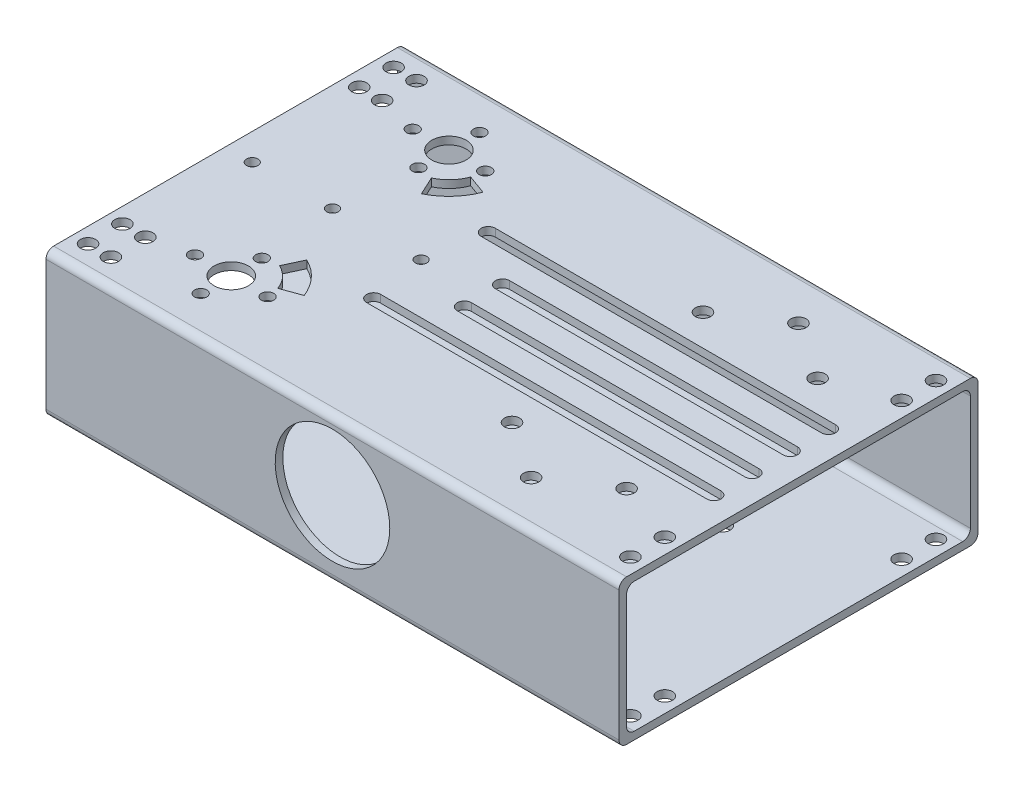
SolidWorks part; units mm, degrees
ref_plane "前视基准面" through (0, 0, 0) normal (0, 0, 1) x (1, 0, 0)
ref_plane "上视基准面" through (0, 0, 0) normal (0, 1, 0) x (1, 0, 0)
ref_plane "右视基准面" through (0, 0, 0) normal (1, 0, 0) x (0, 0, -1)
sketch "草图1" plane through (0, 0, 0) normal (0, 1, 0) x (1, 0, 0)
  line L0 (-118.075, 0) -> (159.1957, 0) construction
  line L1 (0, 69.9051) -> (0, -96.3398) construction
  line L2 (0, 43) -> (0, -43) construction
  line L3 (0, -43) -> (150, -43) construction
  line L4 (150, -43) -> (150, 43) construction
  line L5 (150, 43) -> (0, 43) construction
  line L6 (30, 91.4105) -> (30, -85.9623) construction
  line L7 (30, 28.5) -> (43.2898, 0) construction
  line L8 (30, 28.5) -> (57.9803, 18.316) construction
  line L9 (34.0149, 19.8901) -> (36.2919, 15.0069)
  line L10 (38.9271, 25.2508) -> (43.9901, 23.408)
  line L11 (34.0149, -19.8901) -> (36.2919, -15.0069)
  line L12 (38.9271, -25.2508) -> (43.9901, -23.408)
  circle A0 centre (7, 0) radius 1.5
  circle A1 centre (28, 0) radius 1.5
  circle A2 centre (51.2, 0) radius 1.5
  circle A3 centre (30, -28.5) radius 4.5
  circle A4 centre (30, 28.5) radius 4.5
  circle A5 centre (30, -28.5) radius 8 construction
  circle A6 centre (30, -28.5) radius 9.5 construction
  circle A7 centre (20.5, -28.5) radius 1.6
  circle A8 centre (39.5, -28.5) radius 1.6
  circle A9 centre (30, -36.5) radius 1.6
  circle A10 centre (30, -20.5) radius 1.6
  circle A11 centre (39.5, 28.5) radius 1.6
  circle A12 centre (30, 36.5) radius 1.6
  circle A13 centre (20.5, 28.5) radius 1.6
  circle A14 centre (30, 20.5) radius 1.6
  circle A15 centre (30, 28.5) radius 9.5 construction
  circle A16 centre (30, 28.5) radius 14.888 construction
  arc A17 (38.9271, 25.2508) -> (34.0149, 19.8901) centre (30, 28.5) cw
  arc A18 (43.9901, 23.408) -> (36.2919, 15.0069) centre (29.5132, 28.946) cw
  arc A19 (38.9271, -25.2508) -> (34.0149, -19.8901) centre (30, -28.5) ccw
  arc A20 (43.9901, -23.408) -> (36.2919, -15.0069) centre (29.5132, -28.946) ccw
  point P49 (0, 0)
  point P50 (0, 0)
  point P51 (0, 0)
  point P52 (0, 0)
  point P53 (0, 0)
  point P54 (0, 0)
  point P55 (0, 0)
  dimension "D6" = 57
  dimension "D7" = 9
  dimension "D8" = 16
  dimension "D9" = 19
  dimension "D10" = 3.2
  dimension "D4" = 25
  dimension "D2" = 150
  dimension "D3" = 86
  dimension "D5" = 70
sketch "草图2" plane through (0, 0, 0) normal (1, 0, 0) x (0, 0, -1)
  line L0 (-105.7722, 0) -> (144.3564, 0) construction
  line L1 (-45, 19) -> (45, 19)
  line L2 (-47, 17) -> (-47, -17)
  line L3 (-45, -19) -> (45, -19)
  line L4 (47, 17) -> (47, -17)
  line L5 (-43, 17) -> (43, 17)
  line L6 (-45, 15) -> (-45, -15)
  line L7 (-43, -17) -> (43, -17)
  line L8 (45, 15) -> (45, -15)
  line L9 (0, 59.7941) -> (0, -80.9588) construction
  arc A0 (-45, 15) -> (-43, 17) centre (-43, 15) cw
  arc A1 (-45, -15) -> (-43, -17) centre (-43, -15) ccw
  arc A2 (45, -15) -> (43, -17) centre (43, -15) cw
  arc A3 (43, 17) -> (45, 15) centre (43, 15) cw
  arc A4 (-47, -17) -> (-45, -19) centre (-45, -17) ccw
  arc A5 (47, -17) -> (45, -19) centre (45, -17) cw
  arc A6 (45, 19) -> (47, 17) centre (45, 17) cw
  arc A7 (-45, 19) -> (-47, 17) centre (-45, 17) ccw
  point P19 (-47, -19)
  point P22 (47, -19)
  point P25 (47, 19)
  dimension "D1" = 2
  dimension "D2" = 2
  dimension "D3" = 2
  dimension "D4" = 2
  dimension "D11" = 2
  dimension "D12" = 2
  dimension "D13" = 2
  dimension "D14" = 2
  dimension "D5" = 86
  dimension "D6" = 30
  dimension "D7" = 38
  dimension "D8" = 94
  dimension "D9" = 2
  dimension "D10" = 2
extrude "桶壁" add sketch "草图2" along normal blind 150
extrude "摩擦轮安装孔" cut sketch "草图1" along normal through all
cosmetic thread "装饰螺纹线9" parameters "D2"=9
cosmetic thread "装饰螺纹线10" parameters "D2"=9
cosmetic thread "装饰螺纹线11" parameters "D2"=9
sketch "草图6" plane through (0, 0, 0) normal (0, 0, 1) x (1, 0, 0)
  line L0 (-38.2799, 0) -> (181.5398, 0) construction
  line L1 (75, 53.2108) -> (75, -52.9743) construction
  line L2 (150, 17) -> (0, 17) construction
  line L3 (0, 17) -> (0, -17) construction
  circle A0 centre (75, 1) radius 15
  point P7 (75, 17)
  point P12 (0, 0)
  point P13 (75, 24.4336)
  dimension "D2" = 16
  dimension "D1" = 75
extrude "进弹口" cut sketch "草图6" along normal through all
ref_plane "基准面1" through (0, 0, 47) normal (0, 0, 1) x (1, 0, 0)
ref_plane "基准面2" through (0, 19, 0) normal (0, 1, 0) x (1, 0, 0)
sketch "草图12" plane through (0, 19, 0) normal (0, 1, 0) x (1, 0, 0)
  line L0 (-57.282, 0) -> (202.7295, 0) construction
  line L1 (75, 63.6046) -> (75, -65.9459) construction
  line L2 (150, 45) -> (0, 45) construction
  line L3 (76.4299, 35) -> (194.9244, 35) construction
  line L4 (72.7069, 25) -> (191.2014, 25) construction
  line L5 (61.8628, 15) -> (180.3574, 15) construction
  line L6 (61.8628, 5) -> (180.3574, 5) construction
  line L7 (53.7772, 15) -> (142.8571, 15) construction
  line L8 (53.7772, 16.8495) -> (142.8571, 16.8495)
  line L9 (53.7772, 13.1505) -> (142.8571, 13.1505)
  line L10 (67.5293, 5) -> (142.8571, 5) construction
  line L11 (67.5293, 6.8509) -> (142.8571, 6.8509)
  line L12 (67.5293, 3.1491) -> (142.8571, 3.1491)
  line L13 (53.7772, -15) -> (142.8571, -15) construction
  line L14 (53.7772, -16.8495) -> (142.8571, -16.8495)
  line L15 (53.7772, -13.1505) -> (142.8571, -13.1505)
  line L16 (67.5293, -5) -> (142.8571, -5) construction
  line L17 (67.5293, -6.8509) -> (142.8571, -6.8509)
  line L18 (67.5293, -3.1491) -> (142.8571, -3.1491)
  line L19 (150, 45) -> (150, -45) construction
  circle A0 centre (100, 25) radius 2
  circle A1 centre (130, 25) radius 2
  circle A2 centre (115, 35) radius 2
  arc A3 (53.7772, 16.8495) -> (53.7772, 13.1505) centre (53.7772, 15) ccw
  arc A4 (142.8571, 13.1505) -> (142.8571, 16.8495) centre (142.8571, 15) ccw
  arc A5 (67.5293, 6.8509) -> (67.5293, 3.1491) centre (67.5293, 5) ccw
  arc A6 (142.8571, 3.1491) -> (142.8571, 6.8509) centre (142.8571, 5) ccw
  circle A7 centre (115, -35) radius 2
  circle A8 centre (130, -25) radius 2
  circle A9 centre (100, -25) radius 2
  arc A10 (53.7772, -16.8495) -> (53.7772, -13.1505) centre (53.7772, -15) cw
  arc A11 (142.8571, -13.1505) -> (142.8571, -16.8495) centre (142.8571, -15) cw
  arc A12 (67.5293, -6.8509) -> (67.5293, -3.1491) centre (67.5293, -5) cw
  arc A13 (142.8571, -3.1491) -> (142.8571, -6.8509) centre (142.8571, -5) cw
  point P7 (75, 45)
  point P24 (98.3171, 15)
  point P30 (105.1932, 5)
  point P36 (142.8571, 14.4417)
  point P37 (142.8571, 4.9413)
  point P46 (98.3171, -15)
  point P53 (105.1932, -5)
  point P58 (0, 0)
  point P59 (53.7772, 14.7811)
  point P60 (67.5293, 5.0176)
  point P61 (0, 0)
  dimension "D1" = 20
  dimension "D2" = 50
  dimension "D3" = 35
  dimension "D4" = 10
  dimension "D5" = 10
  dimension "D6" = 10
  dimension "D7" = 5
extrude "炮塔相机模块开孔" cut sketch "草图12" against normal blind 2
ref_plane "基准面3" through (0, -17, 0) normal (0, 1, 0) x (1, 0, 0)
sketch "草图14" plane through (0, -17, 0) normal (0, 1, 0) x (1, 0, 0)
  line L0 (-36.0805, 0) -> (188.2917, 0) construction
  line L1 (75, 58.9221) -> (75, -65.1655) construction
  line L2 (150, 45) -> (0, 45) construction
  line L3 (4, 64.9718) -> (4, -68.4908) construction
  line L4 (0, 45) -> (0, -45) construction
  line L5 (146, 73.9301) -> (146, -65.8637) construction
  line L6 (150, 45) -> (150, -45) construction
  line L7 (10, 63.7061) -> (10, -70.0383) construction
  circle A0 centre (4, 40) radius 2
  circle A1 centre (4, 31) radius 2
  circle A2 centre (4, -31) radius 2
  circle A3 centre (4, -40) radius 2
  circle A4 centre (146, 40) radius 2
  circle A5 centre (146, 31) radius 2
  circle A6 centre (146, -40) radius 2
  circle A7 centre (146, -31) radius 2
  circle A8 centre (10, 40) radius 2
  circle A9 centre (10, 31) radius 2
  circle A10 centre (10, -40) radius 2
  circle A11 centre (10, -31) radius 2
  point P7 (75, 45)
  dimension "D1" = 4
  dimension "D5" = 5
  dimension "D8" = 5
  dimension "D2" = 5
  dimension "D3" = 9
  dimension "D4" = 4
  dimension "D6" = 14
  dimension "D7" = 10
  dimension "D9" = 9
extrude "炮塔前后端装甲安装孔" cut sketch "草图14" against normal through all and the other way through all
sketch "草图15" plane through (0, -17, 0) normal (0, 1, 0) x (1, 0, 0)
  line L0 (-38.4218, 0) -> (191.9337, 0) construction
  line L1 (75, 59.5724) -> (75, -64.6452) construction
  line L2 (150, 45) -> (0, 45) construction
  line L3 (57, 61.7214) -> (57, -55.4724) construction
  line L4 (115, 62.1116) -> (115, -53.1311) construction
  line L5 (142.8571, -13.1505) -> (53.7772, -13.1505) construction
  line L6 (53.7772, 13.1505) -> (142.8571, 13.1505) construction
  circle A0 centre (57, 15.1505) radius 2
  circle A1 centre (57, -15.1505) radius 2
  circle A2 centre (115, 15.1505) radius 2
  circle A3 centre (115, -15.1505) radius 2
  point P7 (75, 45)
  point P24 (0, 0)
  point P25 (0, 0)
  point P26 (0, 0)
  point P27 (0, 0)
  point P28 (0, 0)
  point P29 (0, 0)
  dimension "D1" = 40
  dimension "D2" = 18
extrude "炮塔安装孔" cut sketch "草图15" against normal through all
